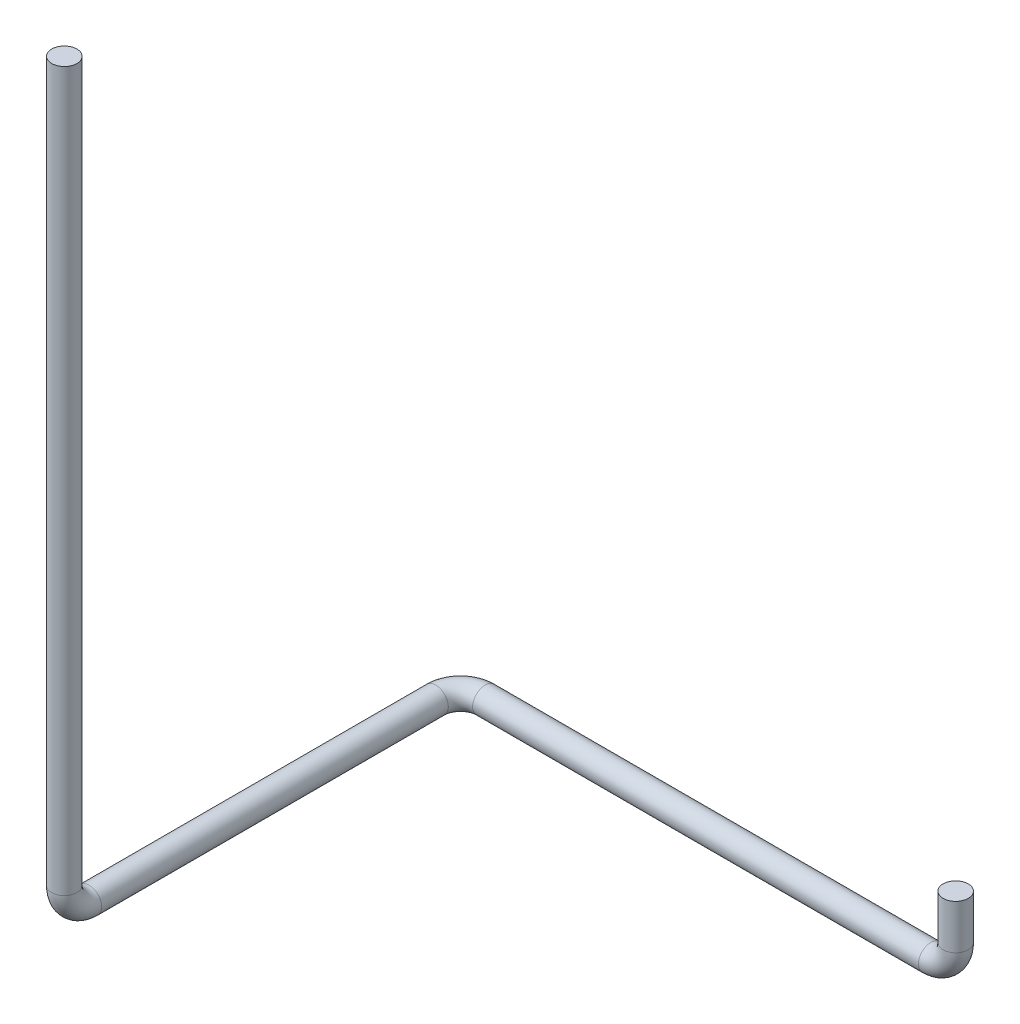
SolidWorks part; units mm, degrees
ref_plane "Alzado" through (0, 0, 0) normal (0, 0, 1) x (1, 0, 0)
ref_plane "Planta" through (0, 0, 0) normal (0, 1, 0) x (1, 0, 0)
ref_plane "Vista lateral" through (0, 0, 0) normal (1, 0, 0) x (0, 0, -1)
sketch "Croquis1" plane through (0, 0, 0) normal (0, 1, 0) x (1, 0, 0)
  circle A0 centre (0, 0) radius 12.7
  dimension "D1" = 25.4
extrude "Saliente-Extruir1" add sketch "Croquis1" against normal blind 20
sketch3d "Croquis3D1"
  line L0 (0, -20, 0) -> (0, -45, 0)
  line L1 (0, -20, 0) -> (0, 0, 0) construction
  line L2 (-25, -70, 0) -> (-475, -70, 0)
  line L3 (-500, -70, 25) -> (-500, -70, 375)
  line L4 (-500, -45, 400) -> (-500, 680, 400)
  arc A0 (-500, -70, 375) -> (-500, -45, 400) centre (-500, -45, 375) ccw
  arc A1 (-475, -70, 0) -> (-500, -70, 25) centre (-475, -70, 25) ccw
  arc A2 (0, -45, 0) -> (-25, -70, 0) centre (-25, -45, 0) ccw
  point P9 (-500, -70, 400)
  point P10 (-525, -45, 375)
  point P13 (-500, -70, 0)
  point P14 (-475, -45, 25)
  point P17 (0, -70, 0)
  point P18 (-25, -45, -25)
  dimension "D5" = 25
  dimension "D6" = 25
  dimension "D1" = 50
  dimension "D2" = 500
  dimension "D3" = 400
  dimension "D4" = 750
sketch "Croquis2" plane through (0, -20, 0) normal (0, -1, 0) x (1, 0, 0)
  circle A0 centre (0, 0) radius 12.7
sweep "Barrer1" add profiles "Croquis2" path "Croquis3D1"
